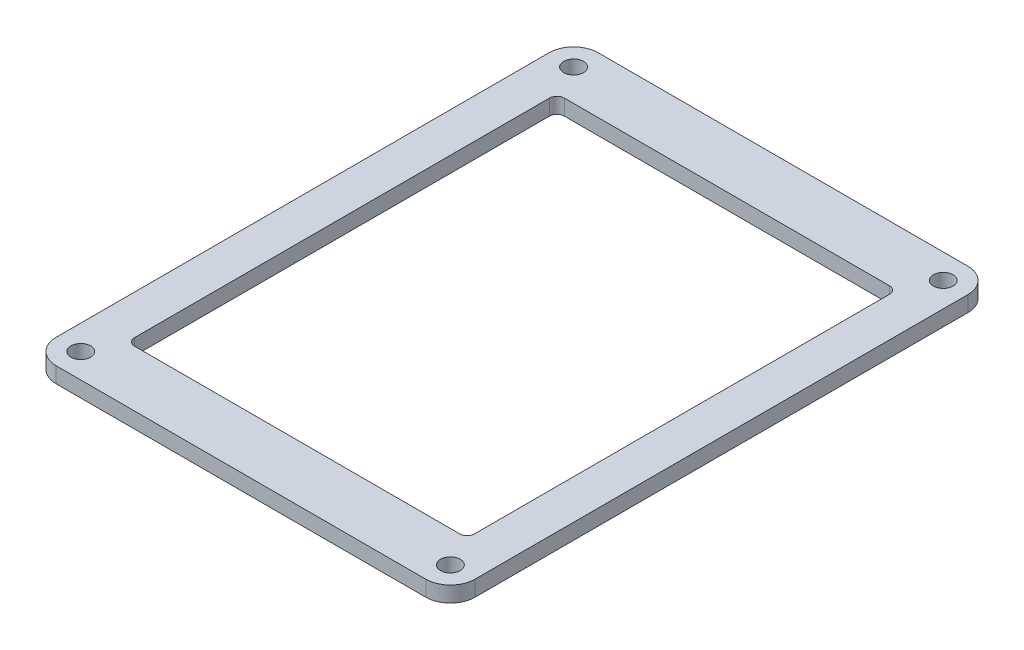
SolidWorks part; units mm, degrees
ref_plane "Front Plane" through (0, 0, 0) normal (0, 0, 1) x (1, 0, 0)
ref_plane "Top Plane" through (0, 0, 0) normal (0, 1, 0) x (1, 0, 0)
ref_plane "Right Plane" through (0, 0, 0) normal (1, 0, 0) x (0, 0, -1)
sketch "Sketch1" plane through (0, 0, 0) normal (0, 1, 0) x (1, 0, 0)
  line L1 (0, 0) -> (85, 0)
  line L2 (0, 0) -> (0, 110)
  line L3 (0, 110) -> (85, 110)
  line L4 (85, 0) -> (85, 110)
  dimension "D1" = 85
  dimension "D2" = 110
extrude "Boss-Extrude1" add sketch "Sketch1" along normal blind 3.175
fillet "Fillet1" radius 5 4 edges at (0, 1.5875, -110) (85, 1.5875, -110) (0, 1.5875, 0) (85, 1.5875, 0)
sketch "Sketch3" plane through (0, 3.175, 0) normal (0, 1, 0) x (1, 0, 0)
  line L0 (0, 55) -> (85, 55) construction
  line L1 (76.991, 11.398) -> (8.009, 11.398)
  line L2 (76.991, 11.398) -> (76.991, 98.602)
  line L3 (76.991, 98.602) -> (8.009, 98.602)
  line L4 (8.009, 11.398) -> (8.009, 98.602)
  line L5 (0, 105) -> (0, 5) construction
  line L6 (85, 5) -> (85, 105) construction
  line L7 (42.5, 0) -> (42.5, 110) construction
  line L8 (5, 0) -> (80, 0) construction
  line L9 (80, 110) -> (5, 110) construction
  point P16 (76.991, 55)
  point P17 (42.5, 11.398)
  dimension "D1" = 87.204
  dimension "D2" = 68.982
extrude "Cut-Extrude3" cut sketch "Sketch3" against normal through all
fillet "Fillet2" radius 1.5 4 edges at (76.991, 1.5875, -11.398) (8.009, 1.5875, -11.398) (76.991, 1.5875, -98.602) (8.009, 1.5875, -98.602)
sketch "Sketch5" plane through (0, 3.175, 0) normal (0, 1, 0) x (1, 0, 0)
  circle A0 centre (5, 5) radius 2
  circle A1 centre (80, 5) radius 2
  circle A2 centre (80, 105) radius 2
  circle A3 centre (5, 105) radius 2
  dimension "D1" = 4
  dimension "D2" = 4
  dimension "D3" = 4
  dimension "D4" = 4
extrude "Cut-Extrude4" cut sketch "Sketch5" against normal through all
